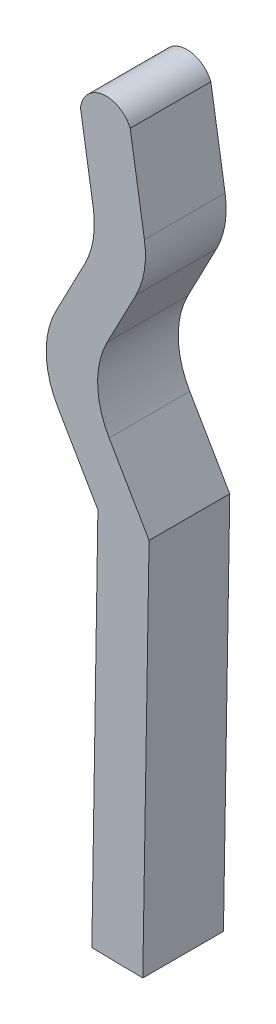
SolidWorks part; units mm, degrees
ref_plane "Спереди" through (0, 0, 0) normal (0, 0, 1) x (1, 0, 0)
ref_plane "Сверху" through (0, 0, 0) normal (0, 1, 0) x (1, 0, 0)
ref_plane "Справа" through (0, 0, 0) normal (1, 0, 0) x (0, 0, -1)
sketch "Эскиз1" plane through (0, 0, 0) normal (0, 0, 1) x (1, 0, 0)
  line L0 (-5.9968, 0.1966) -> (-4.5694, 90.1852)
  line L1 (6, 0) -> (7.4837, 89.9878)
  line L2 (6, 0) -> (-5.9968, 0.1966)
  line L3 (-4.5694, 90.1852) -> (-14.0326, 106.4569)
  line L4 (7.4837, 89.9878) -> (-1.9303, 106.1749)
  line L5 (-14.4754, 125.7631) -> (-7.6731, 138.8005)
  line L6 (-2.3732, 125.4811) -> (4.3627, 138.3913)
  line L7 (6.3828, 150.7842) -> (3.0375, 171.8176)
  line L8 (-5.653, 151.1934) -> (-8.6698, 170.1616)
  arc A3 (-8.6698, 170.1616) -> (3.0375, 171.8176) centre (-2.5967, 169.4385) cw
  arc A4 (-14.4754, 125.7631) -> (-14.0326, 106.4569) centre (3.2562, 116.5116) ccw
  arc A5 (-1.9303, 106.1749) -> (-2.3732, 125.4811) centre (15.3584, 116.2297) cw
  arc A6 (-7.6731, 138.8005) -> (-5.653, 151.1934) centre (-25.4047, 148.052) ccw
  arc A7 (4.3627, 138.3913) -> (6.3828, 150.7842) centre (-13.3689, 147.6427) ccw
  dimension "D1" = 20
extrude "Вытянуть1" add sketch "Эскиз1" along normal blind 19
